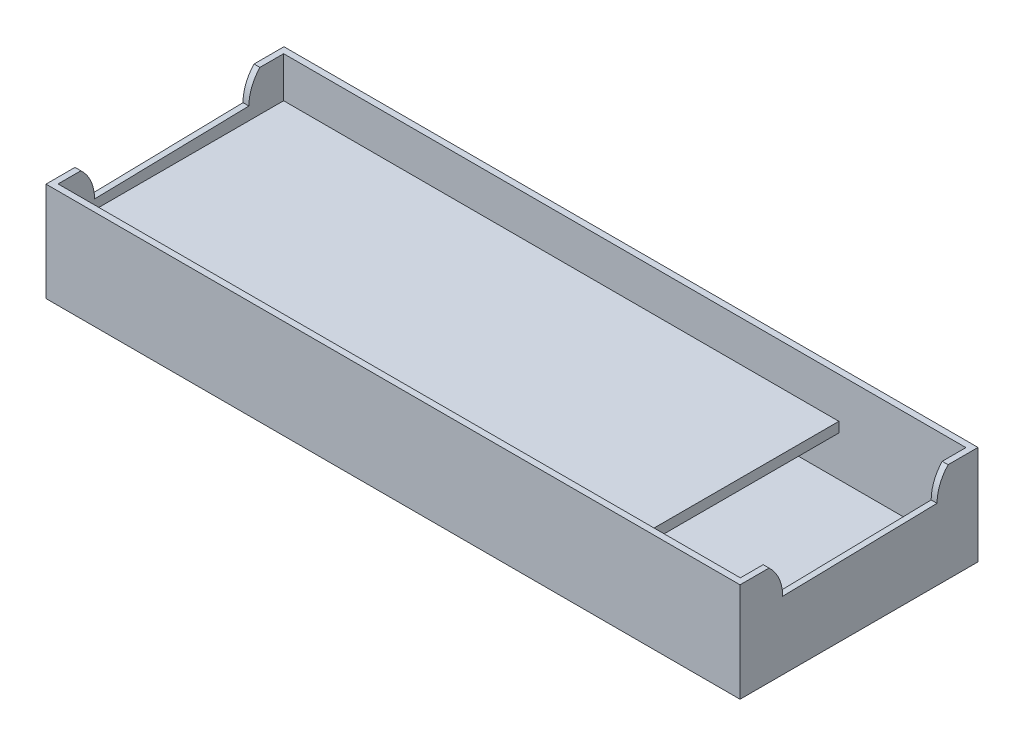
SolidWorks part; units mm, degrees
ref_plane "Front Plane" through (0, 0, 0) normal (0, 0, 1) x (1, 0, 0)
ref_plane "Top Plane" through (0, 0, 0) normal (0, 1, 0) x (1, 0, 0)
ref_plane "Right Plane" through (0, 0, 0) normal (1, 0, 0) x (0, 0, -1)
sketch "Sketch1" plane through (0, 0, 0) normal (0, 1, 0) x (1, 0, 0)
  line L1 (-87.5, 30) -> (87.5, 30)
  line L2 (-87.5, 30) -> (-87.5, -30)
  line L3 (-87.5, -30) -> (87.5, -30)
  line L4 (87.5, 30) -> (87.5, -30)
  line L5 (-87.5, 30) -> (87.5, -30) construction
  line L6 (-87.5, -30) -> (87.5, 30) construction
  point P0 (0, 0)
  dimension "D1" = 175
  dimension "D2" = 60
extrude "Boss-Extrude1" add sketch "Sketch1" along normal blind 25
sketch "Sketch2" plane through (0, 25, 0) normal (0, 1, 0) x (1, 0, 0)
  line L1 (-86.0187, 28.4392) -> (86.0187, 28.4392)
  line L2 (-86.0187, 28.4392) -> (-86.0187, -28.4392)
  line L3 (-86.0187, -28.4392) -> (86.0187, -28.4392)
  line L4 (86.0187, 28.4392) -> (86.0187, -28.4392)
  line L5 (-86.0187, 28.4392) -> (86.0187, -28.4392) construction
  line L6 (-86.0187, -28.4392) -> (86.0187, 28.4392) construction
  point P0 (0, 0)
extrude "Cut-Extrude2" cut sketch "Sketch2" against normal blind 23
sketch "Sketch3" plane through (87.5, 0, 0) normal (1, 0, 0) x (0, 0, -1)
  line L0 (-30, 25) -> (-30, 0) construction
  line L1 (30, 25) -> (30, 0) construction
  line L2 (-19.242, 17.1148) -> (19.673, 17.9513)
  line L3 (-30, 27.8728) -> (-30, 39.0255)
  line L4 (-30, 39.0255) -> (30, 38.1581)
  line L5 (30, 38.1581) -> (30, 25)
  arc A0 (-19.242, 17.1148) -> (-30, 27.8728) centre (-30, 17.1148) ccw
  arc A1 (30, 28.2783) -> (19.673, 17.9513) centre (30, 17.9513) ccw
  point P1 (19.673, 17.9513)
  point P5 (-19.242, 17.1148)
  point P16 (0, 0)
  line M3 (30, 25) -> (-30, 25)
extrude "Cut-Extrude4" cut sketch "Sketch3" against normal through all contours A1 A0 L2 M3
sketch "Sketch5" plane through (-86.0187, 0, 0) normal (1, 0, 0) x (0, 0, -1)
  line L0 (28.4392, 2) -> (28.4392, 25) construction
  line L1 (-28.1805, 14.7226) -> (28.4392, 14.7226)
  line L2 (-28.1805, 14.7226) -> (-28.1805, 12.1794)
  line L3 (-28.1805, 12.1794) -> (28.4392, 12.1794)
  line L4 (28.4392, 14.7226) -> (28.4392, 12.1794)
extrude "Boss-Extrude2" add sketch "Sketch5" along normal blind 140
